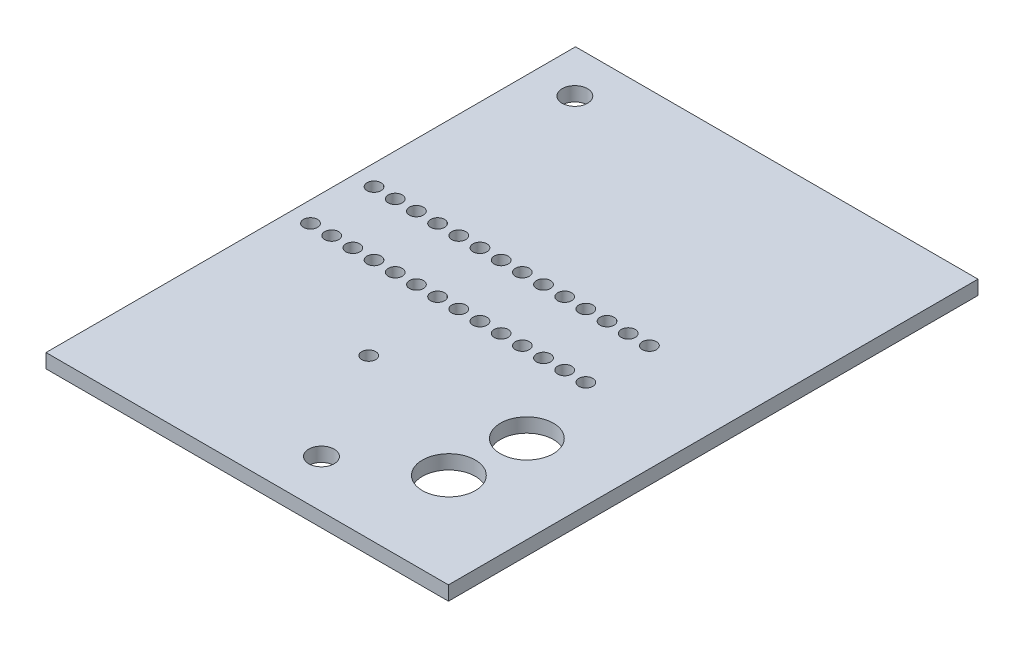
SolidWorks part; units mm, degrees
ref_plane "Front Plane" through (0, 0, 0) normal (0, 0, 1) x (1, 0, 0)
ref_plane "Top Plane" through (0, 0, 0) normal (0, 1, 0) x (1, 0, 0)
ref_plane "Right Plane" through (0, 0, 0) normal (1, 0, 0) x (0, 0, -1)
sketch "Sketch1" plane through (0, 0, 0) normal (0, 1, 0) x (1, 0, 0)
  line L5 (0, 0) -> (48.26, 0)
  line L6 (0, 0) -> (0, 63.5)
  line L7 (0, 63.5) -> (48.26, 63.5)
  line L8 (48.26, 0) -> (48.26, 63.5)
  dimension "D1" = 63.5
  dimension "D2" = 48.26
extrude "Boss-Extrude1" add sketch "Sketch1" along normal blind 1.7
sketch "Sketch3" plane through (0, 1.7, 0) normal (0, 1, 0) x (1, 0, 0)
  circle A0 centre (37.7546, 19.906) radius 3.175
  circle A1 centre (36.9062, 11.4046) radius 3.175
  circle A2 centre (2.4486, 29.2684) radius 0.8382
  circle A3 centre (4.9886, 29.2684) radius 0.8382
  circle A4 centre (7.5286, 29.2684) radius 0.8382
  circle A5 centre (10.0686, 29.2684) radius 0.8382
  circle A6 centre (12.6086, 29.2684) radius 0.8382
  circle A7 centre (15.1486, 29.2684) radius 0.8382
  circle A8 centre (17.6886, 29.2684) radius 0.8382
  circle A9 centre (20.2286, 29.2684) radius 0.8382
  circle A10 centre (22.7686, 29.2684) radius 0.8382
  circle A11 centre (25.3086, 29.2684) radius 0.8382
  circle A12 centre (27.8486, 29.2684) radius 0.8382
  circle A13 centre (30.3886, 29.2684) radius 0.8382
  circle A14 centre (32.9286, 29.2684) radius 0.8382
  circle A15 centre (35.4686, 29.2684) radius 0.8382
  circle A16 centre (4.9886, 36.8884) radius 0.8382
  circle A17 centre (7.5286, 36.8884) radius 0.8382
  circle A18 centre (10.0686, 36.8884) radius 0.8382
  circle A19 centre (12.6086, 36.8884) radius 0.8382
  circle A20 centre (15.1486, 36.8884) radius 0.8382
  circle A21 centre (17.6886, 36.8884) radius 0.8382
  circle A22 centre (20.2286, 36.8884) radius 0.8382
  circle A23 centre (22.7686, 36.8884) radius 0.8382
  circle A24 centre (25.3086, 36.8884) radius 0.8382
  circle A25 centre (27.8486, 36.8884) radius 0.8382
  circle A26 centre (30.3886, 36.8884) radius 0.8382
  circle A27 centre (32.9286, 36.8884) radius 0.8382
  circle A28 centre (35.4686, 36.8884) radius 0.8382
  circle A29 centre (2.4486, 36.8884) radius 0.8382
  circle A30 centre (27.3101, 5.7201) radius 1.524
  circle A31 centre (5.0673, 58.3463) radius 1.524
  circle A32 centre (19.6723, 19.0271) radius 0.8382
  dimension "D1" = 14
  dimension "D2" = 2
extrude "Cut-Extrude1" cut sketch "Sketch3" against normal through all
